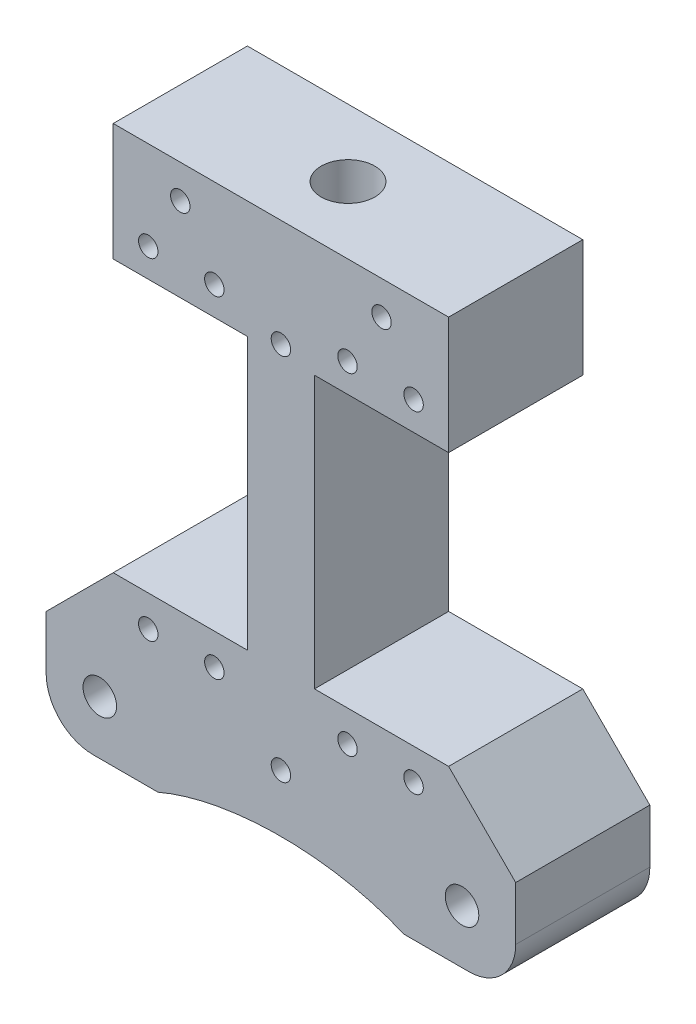
SolidWorks part; units mm, degrees
ref_plane "前视基准面" through (0, 0, 0) normal (0, 0, 1) x (1, 0, 0)
ref_plane "上视基准面" through (0, 0, 0) normal (0, 1, 0) x (1, 0, 0)
ref_plane "右视基准面" through (0, 0, 0) normal (1, 0, 0) x (0, 0, -1)
sketch "草图1" plane through (0, 0, 0) normal (0, 0, 1) x (1, 0, 0)
  line L1 (-25, -40) -> (25, -40)
  line L2 (-25, -40) -> (-25, 40)
  line L3 (-25, 40) -> (25, 40)
  line L4 (25, -40) -> (25, 40)
  line L5 (-25, -40) -> (25, 40) construction
  line L6 (-25, 40) -> (25, -40) construction
  point P0 (0, 0)
  dimension "D1" = 50
  dimension "D2" = 80
extrude "凸台-拉伸1" add sketch "草图1" along normal blind 20
sketch "草图2" plane through (0, 0, 20) normal (0, 0, 1) x (1, 0, 0)
  line L0 (-25, 40) -> (-25, -40) construction
  line L1 (-45, -20) -> (-5, -20)
  line L2 (-45, -20) -> (-45, 20)
  line L3 (-45, 20) -> (-5, 20)
  line L4 (-5, -20) -> (-5, 20)
  line L5 (-45, -20) -> (-5, 20) construction
  line L6 (-45, 20) -> (-5, -20) construction
  line L7 (0, 40) -> (0, -40) construction
  line L8 (25, 40) -> (-25, 40) construction
  line L9 (-25, -40) -> (25, -40) construction
  line L10 (45, 20) -> (5, 20)
  line L11 (5, -20) -> (5, 20)
  line L12 (45, -20) -> (5, -20)
  line L13 (45, -20) -> (45, 20)
  point P0 (-25, 0)
  dimension "D1" = 20
  dimension "D2" = 40
extrude "切除-拉伸1" cut sketch "草图2" against normal blind 48 and the other way blind 18
sketch "草图3" plane through (0, 0, 20) normal (0, 0, 1) x (1, 0, 0)
  line L0 (0, -40) -> (0, 40) construction
  line L1 (-25, -40) -> (25, -40) construction
  line L2 (25, 40) -> (-25, 40) construction
  circle A0 centre (9.925, -24.6611) radius 1.45
  circle A1 centre (19.775, -24.6611) radius 1.45
  circle A2 centre (9.925, 24.7611) radius 1.45
  circle A3 centre (19.775, 24.7611) radius 1.45
  circle A4 centre (-9.925, 24.7611) radius 1.45
  circle A5 centre (-19.775, 24.7611) radius 1.45
  circle A6 centre (-9.925, -24.6611) radius 1.45
  circle A7 centre (-19.775, -24.6611) radius 1.45
  dimension "D1" = 2.9
  dimension "D2" = 2.9
  dimension "D3" = 2.9
  dimension "D4" = 2.9
extrude "切除-拉伸2" cut sketch "草图3" against normal blind 50 and the other way blind 25
sketch "草图5" plane through (25, 0, 0) normal (1, 0, 0) x (0, 0, -1)
  line L1 (0, -40) -> (-20, -40)
  line L2 (0, -40) -> (0, -20)
  line L3 (0, -20) -> (-20, -20)
  line L4 (-20, -40) -> (-20, -20)
extrude "凸台-拉伸3" add sketch "草图5" along normal blind 10
sketch "草图6" plane through (-25, 0, 0) normal (-1, 0, 0) x (0, 0, 1)
  line L1 (20, -40) -> (0, -40)
  line L2 (20, -40) -> (20, -20)
  line L3 (20, -20) -> (0, -20)
  line L4 (0, -40) -> (0, -20)
extrude "凸台-拉伸4" add sketch "草图6" along normal blind 10
sketch "草图11" plane through (0, 0, 20) normal (0, 0, 1) x (1, 0, 0)
  line L1 (35, -40) -> (-35, -40)
  line L2 (35, -40) -> (35, -45)
  line L3 (35, -45) -> (-35, -45)
  line L4 (-35, -40) -> (-35, -45)
  dimension "D1" = 5
extrude "凸台-拉伸6" add sketch "草图11" against normal up to surface (20 mm away) up to face at (-11.375, 24.7611, 0)
sketch "草图12" plane through (0, 0, 20) normal (0, 0, 1) x (1, 0, 0)
  line L0 (-35, -45) -> (35, -45) construction
  line L1 (35, -20) -> (35, -45) construction
  line L2 (0, -45) -> (0, 40) construction
  line L3 (25, 40) -> (-25, 40) construction
  circle A0 centre (27, -37) radius 2.5
  circle A1 centre (-27, -37) radius 2.5
  dimension "D1" = 5
  dimension "D2" = 8
  dimension "D3" = 8
extrude "切除-拉伸6" cut sketch "草图12" against normal blind 26
chamfer "倒角1" distance 10 angle 45 2 edges at (-35, -20, 10) (35, -20, 10)
sketch "草图14" plane through (0, 0, 20) normal (0, 0, 1) x (1, 0, 0)
  line L0 (-35, -45) -> (35, -45) construction
  line L1 (12.5, -37.5) -> (-12.5, -37.5)
  line L2 (12.5, -37.5) -> (12.5, -52.5)
  line L3 (12.5, -52.5) -> (-12.5, -52.5)
  line L4 (-12.5, -37.5) -> (-12.5, -52.5)
  line L5 (12.5, -37.5) -> (-12.5, -52.5) construction
  line L6 (12.5, -52.5) -> (-12.5, -37.5) construction
  point P0 (0, -45)
  dimension "D1" = 25
  dimension "D2" = 15
extrude "凸台-拉伸7" add sketch "草图14" against normal up to surface (20 mm away) up to face at (24.5, -37, 0)
chamfer "倒角2" distance 3 angle 45 2 edges at (12.5, -52.5, 10) (-12.5, -52.5, 10)
chamfer "倒角3" distance 2 angle 45 2 edges at (0, -52.5, 0) (0, -52.5, 20)
sketch "草图17" plane through (0, 0, 0) normal (0, 0, -1) x (-1, 0, 0)
  line L0 (-25, 40) -> (25, 40) construction
  circle A0 centre (15, 33) radius 1.45
  circle A1 centre (-15, 33) radius 1.45
  dimension "D1" = 2.9
  dimension "D2" = 2.9
  dimension "D3" = 7
  dimension "D4" = 7
extrude "切除-拉伸8" cut sketch "草图17" against normal blind 57 and the other way blind 30
sketch "草图18" plane through (0, 0, 20) normal (0, 0, 1) x (1, 0, 0)
  line L1 (12.5, -45) -> (-13.5672, -45)
  line L2 (12.5, -45) -> (12.5, -58.5066)
  line L3 (12.5, -58.5066) -> (-13.5672, -58.5066)
  line L4 (-13.5672, -45) -> (-13.5672, -58.5066)
extrude "切除-拉伸9" cut sketch "草图18" against normal blind 42
sketch "草图19" plane through (0, 0, 20) normal (0, 0, 1) x (1, 0, 0)
  line L1 (0, -113.8116) -> (0, 0) construction
  ellipse E0 centre (0, -56.9058) end of major axis (28.9992, -56.9058) minor radius 15.3607
extrude "切除-拉伸10" cut sketch "草图19" against normal blind 42
fillet "圆角1" radius 7 2 edges at (35, -45, 10) (-35, -45, 10)
sketch "草图20" plane through (0, 0, 0) normal (0, 0, -1) x (-1, 0, 0)
  circle A0 centre (27, -37) radius 2.5
  circle A1 centre (27, -37) radius 1.75
  circle A2 centre (-27, -37) radius 2.5
  circle A3 centre (-27, -37) radius 1.75
  dimension "D1" = 3.5
  dimension "D2" = 3.5
extrude "凸台-拉伸8" add sketch "草图20" against normal blind 3.5 from offset 8.5 offset against normal yes
sketch "草图21" plane through (0, 0, 0) normal (0, 0, -1) x (-1, 0, 0)
  line L0 (0, -41.5451) -> (0, 40) construction
  line L1 (-25, 20) -> (-5, 20)
  line L2 (-25, 20) -> (-25, 20.5)
  line L3 (-25, 20.5) -> (-5, 20.5)
  line L4 (-5, 20) -> (-5, 20.5)
  line L5 (-25, 40) -> (25, 40) construction
  line L6 (5, 20) -> (5, 20.5)
  line L7 (25, 20.5) -> (5, 20.5)
  line L8 (25, 20) -> (25, 20.5)
  line L9 (25, 20) -> (5, 20)
  ellipse E0 centre (0, -56.9058) end of major axis (28.9992, -56.9058) minor radius 15.3607 (18.3235, -45) -> (-18.3235, -45) ccw construction
  dimension "D1" = 0.5
extrude "切除-拉伸11" cut sketch "草图21" against normal blind 31
sketch "草图22" plane through (0, 0, 0) normal (0, 0, -1) x (-1, 0, 0)
  line L0 (25, 40) -> (25, 20.5) construction
  line L1 (-25, 40) -> (25, 40)
  line L2 (-25, 40) -> (-25, 38)
  line L3 (-25, 38) -> (25, 38)
  line L4 (25, 40) -> (25, 38)
  dimension "D1" = 2
extrude "切除-拉伸12" cut sketch "草图22" against normal blind 31
sketch "草图24" plane through (0, 0, 0) normal (0, 0, -1) x (-1, 0, 0)
  circle A0 centre (0, -33) radius 1.45
  dimension "D1" = 2.9
extrude "切除-拉伸14" cut sketch "草图24" against normal blind 53 and the other way blind 14
sketch "草图25" plane through (0, 0, 0) normal (0, 0, -1) x (-1, 0, 0)
  circle A0 centre (0, 22) radius 1.45
  circle A1 centre (0, -33) radius 1.45 construction
  dimension "D1" = 2.9
  dimension "D2" = 55
extrude "切除-拉伸16" cut sketch "草图25" against normal blind 26
sketch "草图26" plane through (0, 38, 0) normal (0, 1, 0) x (1, 0, 0)
  circle A0 centre (0, -10) radius 4
  dimension "D1" = 8
extrude "切除-拉伸17" cut sketch "草图26" against normal blind 10
